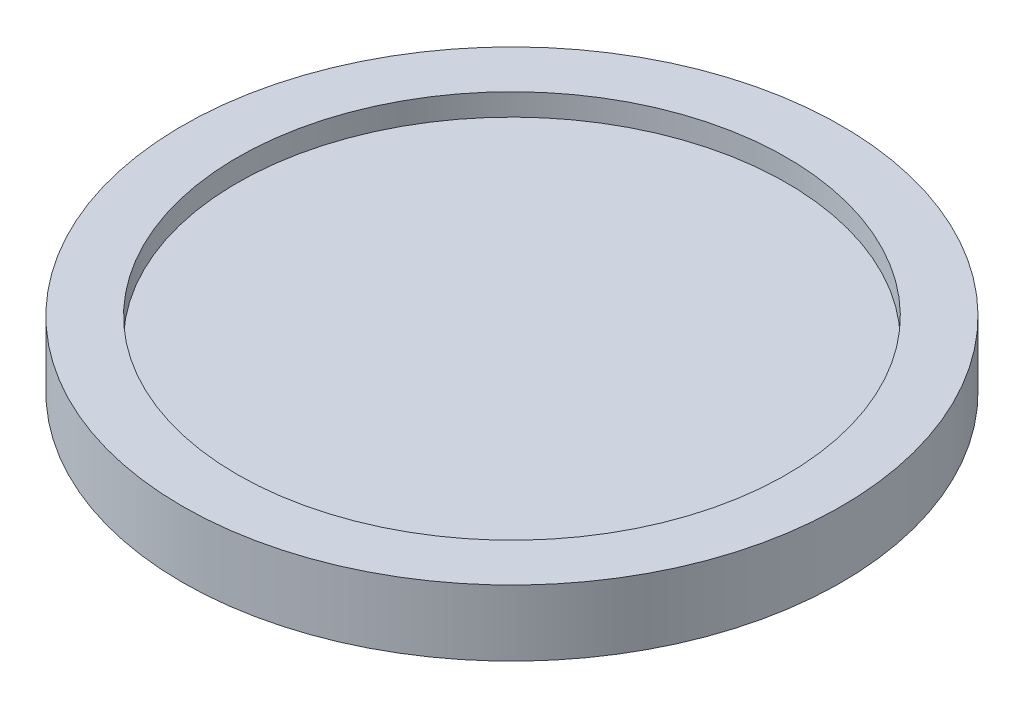
SolidWorks part; units mm, degrees
ref_plane "前视基准面" through (0, 0, 0) normal (0, 0, 1) x (1, 0, 0)
ref_plane "上视基准面" through (0, 0, 0) normal (0, 1, 0) x (1, 0, 0)
ref_plane "右视基准面" through (0, 0, 0) normal (1, 0, 0) x (0, 0, -1)
other "Configuration Table"
sketch "草图1" plane through (0, 0, 0) normal (0, 1, 0) x (1, 0, 0)
  circle A0 centre (0, 0) radius 30
  dimension "D1" = 60
extrude "凸台-拉伸3" add sketch "草图1" along normal blind 6 contours A0
sketch "草图4" plane through (0, 0, 0) normal (0, 1, 0) x (1, 0, 0)
  circle A0 centre (0, 0) radius 25
  dimension "D1" = 50
sketch "草图6" plane through (0, 0, 0) normal (0, -1, 0) x (1, 0, 0)
  circle A1 centre (0, 0) radius 25
  dimension "D1" = 50
extrude "切除-拉伸1" cut sketch "草图6" against normal blind 2
extrude "切除-拉伸2" cut sketch "草图4" against normal blind 2 from surface at 6 contours A0 starting at face at (0, 6, 30)
sketch "草图7" plane through (0, 4, 0) normal (0, 1, 0) x (1, 0, 0)
  circle A0 centre (0, 0) radius 2
sketch "草图8" plane through (0, 2, 0) normal (0, -1, 0) x (-1, 0, 0)
  circle A0 centre (0, 0) radius 6
extrude "凸台-拉伸5" add sketch "草图8" along normal blind 10 contours A0
sketch "草图10" plane through (0, -8, 0) normal (0, -1, 0) x (-1, 0, 0)
  circle A0 centre (0, 0) radius 2
extrude "切除-拉伸6" cut sketch "草图10" against normal blind 10
